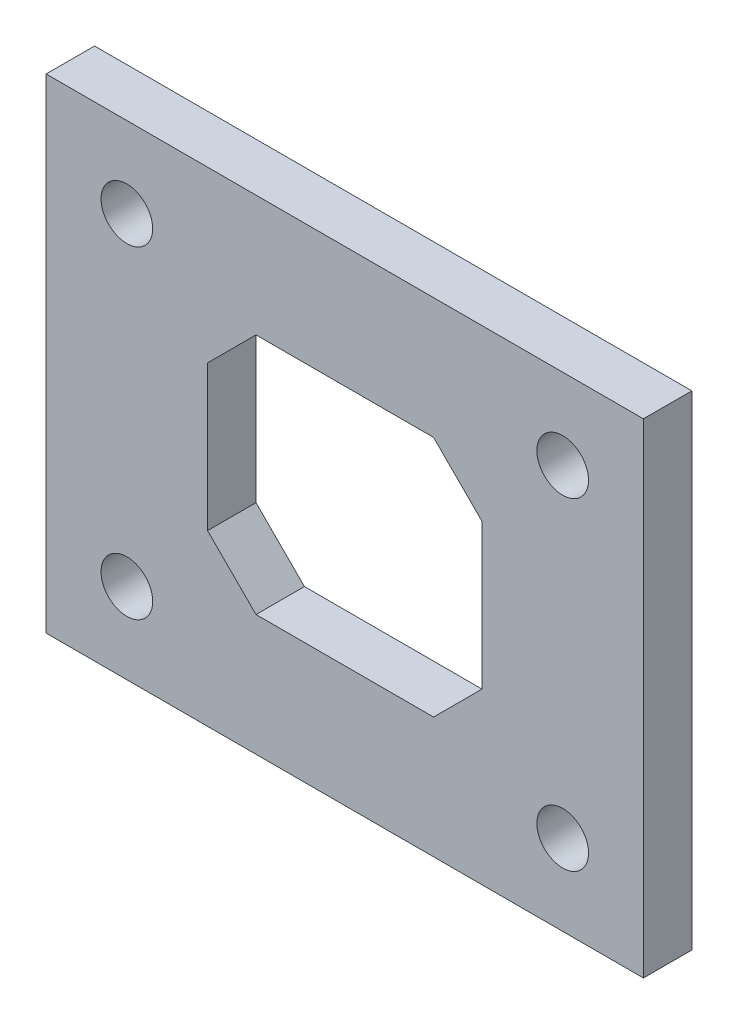
SolidWorks part; units mm, degrees
ref_plane "正面" through (0, 0, 0) normal (0, 0, 1) x (1, 0, 0)
ref_plane "平面" through (0, 0, 0) normal (0, 1, 0) x (1, 0, 0)
ref_plane "右側面" through (0, 0, 0) normal (1, 0, 0) x (0, 0, -1)
sketch "ｽｹｯﾁ1" plane through (0, 0, 0) normal (0, 0, 1) x (1, 0, 0)
  line L1 (-18.5, -60) -> (18.5, -60)
  line L2 (-18.5, -60) -> (-18.5, 60)
  line L3 (-18.5, 60) -> (18.5, 60)
  line L4 (18.5, -60) -> (18.5, 60)
  line L5 (-18.5, -60) -> (18.5, 60) construction
  line L6 (-18.5, 60) -> (18.5, -60) construction
  line L8 (-18.5, 25) -> (-18.5, -25)
  circle A0 centre (-13.5, 55) radius 1.6
  circle A1 centre (-13.5, 35) radius 1.6
  circle A2 centre (13.5, 55) radius 1.6
  circle A3 centre (13.5, 35) radius 1.6
  circle A4 centre (-13.5, -35) radius 3
  circle A5 centre (-13.5, -55) radius 1.6
  circle A6 centre (13.5, -35) radius 3
  circle A7 centre (13.5, -55) radius 1.6
  point P0 (0, 0)
  point P23 (0, 0)
  point P25 (0, 0)
  dimension "D3" = 3.2
  dimension "D4" = 3.2
  dimension "D5" = 3.2
  dimension "D6" = 3.2
  dimension "D7" = 6
  dimension "D8" = 3.2
  dimension "D9" = 6
  dimension "D10" = 3.2
  dimension "D11" = 5
  dimension "D12" = 5
  dimension "D13" = 5
  dimension "D14" = 5
  dimension "D15" = 20
  dimension "D16" = 5
  dimension "D17" = 5
  dimension "D18" = 20
  dimension "D19" = 20
  dimension "D20" = 5
  dimension "D21" = 5
  dimension "D22" = 20
  dimension "D23" = 5
  dimension "D24" = 5
  dimension "D25" = 20
  dimension "D26" = 5
  dimension "D27" = 5
  dimension "D1" = 120
  dimension "D2" = 37
extrude "ﾎﾞｽ - 押し出し1" add sketch "ｽｹｯﾁ1" along normal blind 3
sketch "ｽｹｯﾁ2" plane through (0, 0, 3) normal (0, 0, 1) x (1, 0, 0)
  line L0 (18.5, -60) -> (18.5, 60) construction
  line L1 (-18.5, -60) -> (18.5, -60)
  line L2 (-18.5, -60) -> (-18.5, 30)
  line L3 (-18.5, 30) -> (18.5, 30)
  line L4 (18.5, -60) -> (18.5, 30)
  line L5 (-18.5, 60) -> (18.5, 60) construction
  dimension "D1" = 30
extrude "ｶｯﾄ - 押し出し1" cut sketch "ｽｹｯﾁ2" against normal blind 3
sketch "ｽｹｯﾁ3" plane through (0, 0, 0) normal (0, 0, -1) x (-1, 0, 0)
  line L0 (-18.5, 30) -> (-18.5, 60) construction
  line L1 (-8.5, 52.5) -> (8.5, 52.5)
  line L2 (-8.5, 52.5) -> (-8.5, 37.5)
  line L3 (-8.5, 37.5) -> (8.5, 37.5)
  line L4 (8.5, 52.5) -> (8.5, 37.5)
  line L5 (18.5, 30) -> (18.5, 60) construction
  line L6 (18.5, 60) -> (-18.5, 60) construction
  point P10 (8.5, 45)
  dimension "D1" = 10
  dimension "D2" = 10
  dimension "D3" = 15
  dimension "D4" = 15
extrude "ｶｯﾄ - 押し出し2" cut sketch "ｽｹｯﾁ3" against normal through all
chamfer "面取り1" distance 3 angle 45 4 edges at (-8.5, 37.5, 1.5) (8.5, 37.5, 1.5) (8.5, 52.5, 1.5) (-8.5, 52.5, 1.5)
